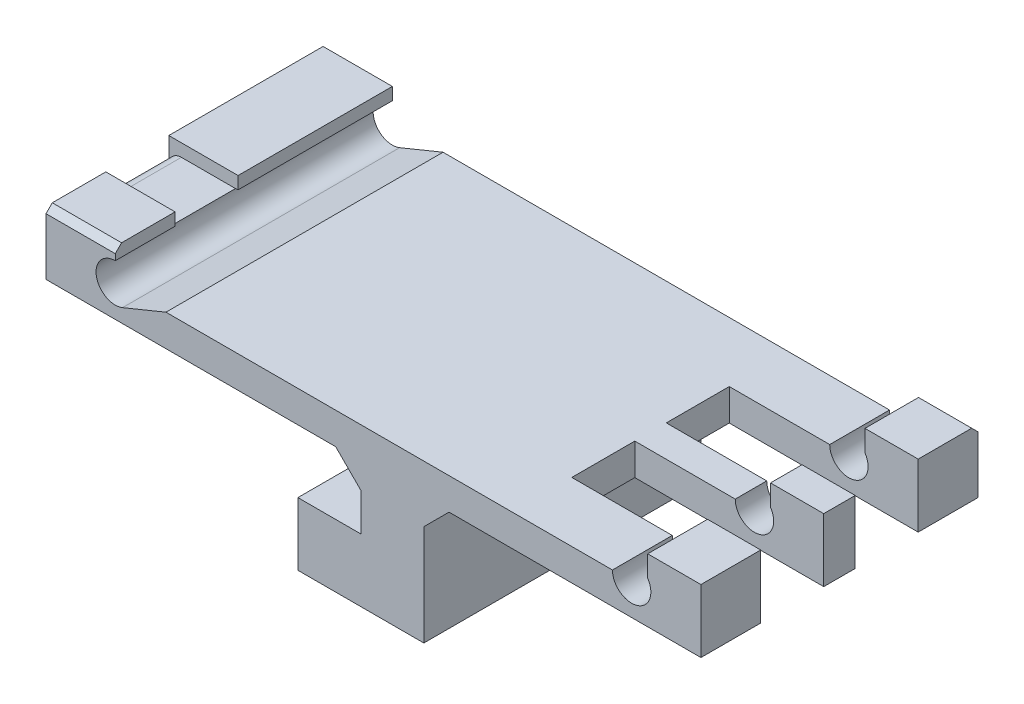
SolidWorks part; units mm, degrees
ref_plane "前视基准面" through (0, 0, 0) normal (0, 0, 1) x (1, 0, 0)
ref_plane "上视基准面" through (0, 0, 0) normal (0, 1, 0) x (1, 0, 0)
ref_plane "右视基准面" through (0, 0, 0) normal (1, 0, 0) x (0, 0, -1)
other "Configuration Table"
sketch "草图1" plane through (0, 0, 0) normal (0, 1, 0) x (1, 0, 0)
  line L1 (-52, -22) -> (52, -22)
  line L2 (-52, -22) -> (-52, 22)
  line L3 (-52, 22) -> (52, 22)
  line L4 (52, -22) -> (52, 22)
  line L5 (-52, -22) -> (52, 22) construction
  line L6 (-52, 22) -> (52, -22) construction
  point P0 (0, 0)
  dimension "D1" = 104
  dimension "D2" = 44
extrude "凸台-拉伸1" add sketch "草图1" along normal blind 10 and the other way blind 0.045
sketch "草图2" plane through (0, 0, -22) normal (0, 0, -1) x (-1, 0, 0)
  line L1 (12, -10.045) -> (2, -10.045)
  line L7 (2, -10.045) -> (2, -0.045)
  line L12 (-52, -0.045) -> (52, -0.045) construction
  line L13 (-8, -0.045) -> (12, -0.045)
  line L14 (-8, -0.045) -> (-8, -20.045)
  line L15 (-8, -20.045) -> (12, -20.045)
  line L16 (12, -0.045) -> (12, -20.045)
  line L17 (52, 10) -> (52, -0.045) construction
  line L18 (-8, -0.045) -> (2, -0.045)
  line L19 (-8, -0.045) -> (-8, -10.5251)
  dimension "D1" = 10
  dimension "D2" = 8
  dimension "D3" = 10
  dimension "D4" = 40
extrude "凸台-拉伸2" add sketch "草图2" against normal up to surface (44 mm away) up to face at (0, 4.9775, 22)
sketch "草图3" plane through (0, 0, 22) normal (0, 0, 1) x (1, 0, 0)
  line L0 (-52, 4.9775) -> (52, 4.9775)
  line L1 (-52, 10) -> (-52, -0.045) construction
  line L2 (52, 10) -> (52, -0.045) construction
  line L3 (0, 0) -> (0, 10) construction
  line L4 (-52, 10) -> (52, 10) construction
  line L6 (-52, 5.0775) -> (52, 5.0775)
  line L7 (-52, 5.0775) -> (-52, 4.8775)
  line L8 (-52, 4.8775) -> (52, 4.8775)
  line L9 (52, 5.0775) -> (52, 4.8775)
  line L10 (-52, 5.0775) -> (52, 4.8775) construction
  line L11 (-52, 4.8775) -> (52, 5.0775) construction
  circle A0 centre (41, 4.9775) radius 3.05
  circle A1 centre (-41, 4.9775) radius 3.05
  point P10 (0, 4.9775)
  dimension "D2" = 6.1
  dimension "D1" = 82
  dimension "D3" = 0.2
extrude "切除-拉伸1" cut sketch "草图3" against normal up to surface (44 mm away) contours L0 A1 L6 | L0 A1 L8 | L8 A1 | L6 A1 | L0 A0 L6 | L0 A0 L8 | L8 A0 | L6 A0 up to face at (-1.2, -4.036, -22)
sketch "草图4" plane through (0, -0.045, 0) normal (0, -1, 0) x (1, 0, 0)
  line L0 (-52, 0) -> (52, 0) construction
  line L5 (-2, -22) -> (-52, -22) construction
  line L7 (52, 22) -> (52, -22) construction
  line L8 (-52, -22) -> (-52, 22) construction
  line L12 (-32, -17) -> (32, -17)
  line L13 (-32, -17) -> (-32, 17)
  line L14 (-32, 17) -> (32, 17)
  line L15 (32, -17) -> (32, 17)
  line L16 (-32, -17) -> (32, 17) construction
  line L17 (-32, 17) -> (32, -17) construction
  line L21 (8, 22) -> (-12, 22)
  line L22 (-12, 22) -> (-12, -22)
  line L23 (-12, -22) -> (8, -22)
  line L24 (8, -22) -> (8, 22)
  line L25 (8, 22) -> (-12, 22)
  line L26 (-12, 22) -> (-12, -22)
  line L27 (-12, -22) -> (8, -22)
  line L28 (8, -22) -> (8, 22)
  point P8 (0, 0)
  dimension "D1" = 20
  dimension "D2" = 20
  dimension "D3" = 5
  dimension "D4" = 0
extrude "切除-拉伸2" [suppressed] cut sketch "草图4" against normal up to surface (10.045 mm away)
sketch "草图6" plane through (37.3205, -20.045, 0) normal (0, 1, 0) x (-1, 0, 0)
  line L5 (34.3205, -17) -> (34.3205, 17)
  line L10 (49.3205, 22) -> (29.3205, 22)
  line L11 (49.3205, -22) -> (49.3205, 22)
  line L12 (29.3205, -22) -> (49.3205, -22)
  line L13 (29.3205, 22) -> (29.3205, -22)
  line L14 (49.3205, 22) -> (29.3205, 22)
  line L15 (49.3205, -22) -> (49.3205, 22)
  line L16 (29.3205, -22) -> (49.3205, -22)
  line L17 (29.3205, 22) -> (29.3205, -22)
  line L18 (5.3205, -17) -> (69.3205, -17)
  line L19 (69.3205, -17) -> (69.3205, 17)
  line L20 (69.3205, 17) -> (5.3205, 17)
  line L21 (5.3205, 17) -> (5.3205, -17)
  line L22 (5.3205, -17) -> (69.3205, -17)
  line L23 (69.3205, -17) -> (69.3205, 17)
  line L24 (69.3205, 17) -> (5.3205, 17)
  line L25 (5.3205, 17) -> (5.3205, -17)
  dimension "D1" = 0
  dimension "D3" = 5
  dimension "D2" = 0
extrude "切除-拉伸3" [suppressed] cut sketch "草图6" along normal up to surface (30.045 mm away) contours L24 L15 L22 L5
chamfer "倒角1" [suppressed] distance 4 angle 45
chamfer "倒角2" [suppressed] distance 4 angle 45
sketch "草图7" plane through (0, -0.045, 0) normal (0, -1, 0) x (1, 0, 0)
  line L1 (46.3158, 18.5731) -> (-46.3158, 18.5731)
  line L2 (46.3158, 18.5731) -> (46.3158, -18.5731)
  line L3 (46.3158, -18.5731) -> (-46.3158, -18.5731)
  line L4 (-46.3158, 18.5731) -> (-46.3158, -18.5731)
  line L5 (46.3158, 18.5731) -> (-46.3158, -18.5731) construction
  line L6 (46.3158, -18.5731) -> (-46.3158, 18.5731) construction
  line L7 (36.0618, 18.5731) -> (-36.0618, 18.5731)
  line L8 (36.0618, 18.5731) -> (36.0618, -18.5731)
  line L9 (36.0618, -18.5731) -> (-36.0618, -18.5731)
  line L10 (-36.0618, 18.5731) -> (-36.0618, -18.5731)
  line L11 (36.0618, 18.5731) -> (-36.0618, -18.5731) construction
  line L12 (36.0618, -18.5731) -> (-36.0618, 18.5731) construction
  point P0 (0, 0)
  point P6 (0, 0)
chamfer "倒角4" distance 4 angle 45 2 edges at (8, -0.045, 0) (-2, -0.045, 0)
sketch "草图8" plane through (0, -0.045, 0) normal (0, -1, 0) x (1, 0, 0)
  line L0 (-52, 0) -> (52, 0) construction
  line L1 (-32, -17) -> (32, -17)
  line L2 (-32, -17) -> (-32, 17)
  line L3 (-32, 17) -> (32, 17)
  line L4 (32, -17) -> (32, 17)
  line L5 (-32, -17) -> (32, 17) construction
  line L6 (-32, 17) -> (32, -17) construction
  line L7 (-47.5, -17) -> (47.5, -17)
  line L8 (-47.5, -17) -> (-47.5, 17)
  line L9 (-47.5, 17) -> (47.5, 17)
  line L10 (47.5, -17) -> (47.5, 17)
  line L11 (-47.5, -17) -> (47.5, 17) construction
  line L12 (-47.5, 17) -> (47.5, -17) construction
  line L13 (-52, -22) -> (-52, 22) construction
  line L14 (52, 22) -> (52, -22) construction
  circle A0 centre (-47.5, 17) radius 1.575
  circle A1 centre (-32, 17) radius 1.575
  circle A2 centre (32, 17) radius 1.575
  circle A3 centre (47.5, 17) radius 1.575
  circle A4 centre (-47.5, -17) radius 1.575
  circle A5 centre (-32, -17) radius 1.575
  circle A6 centre (32, -17) radius 1.575
  circle A7 centre (47.5, -17) radius 1.575
  point P0 (0, 0)
  point P6 (0, 0)
  dimension "D4" = 3.15
  dimension "D1" = 34
  dimension "D2" = 64
  dimension "D3" = 95
extrude "切除-拉伸4" [suppressed] cut sketch "草图8" against normal up to surface (10.045 mm away) contours L9 A1 L2 | L2 A1 L3 | L3 A1 L9 | L9 A2 | L4 A2 L9 | L9 A2 L4 | A6 L7 | A6 L4 L7 | A6 L7 L4 | A5 L1 L7 | A5 L7 L2 | A5 L2 L1
sketch "草图9" plane through (0, -0.045, 0) normal (0, -1, 0) x (1, 0, 0)
  line L0 (52, 22) -> (52, -22) construction
  line L1 (22, 12.5) -> (52, 12.5)
  line L2 (22, 12.5) -> (22, 2.5)
  line L3 (22, 2.5) -> (52, 2.5)
  line L4 (52, 12.5) -> (52, 2.5)
  line L5 (22, 12.5) -> (52, 2.5) construction
  line L6 (22, 2.5) -> (52, 12.5) construction
  line L7 (0, 0) -> (50, 0) construction
  line L9 (22, -2.5) -> (52, -2.5)
  line L10 (22, -2.5) -> (22, -12.5)
  line L11 (22, -12.5) -> (52, -12.5)
  line L12 (52, -2.5) -> (52, -12.5)
  line L13 (22, -2.5) -> (52, -12.5) construction
  line L14 (22, -12.5) -> (52, -2.5) construction
  point P0 (37, 7.5)
  point P11 (37, -7.5)
  dimension "D1" = 10
  dimension "D2" = 30
  dimension "D3" = 10
  dimension "D4" = 5
extrude "切除-拉伸5" cut sketch "草图9" against normal up to surface (10.045 mm away) up to face at (0, 10, 0)
sketch "草图10" plane through (22, 0, 0) normal (1, 0, 0) x (0, 0, -1)
  line L0 (-12.5, 8) -> (-2.5, 8)
  line L4 (-12.5, -0.045) -> (-2.5, -0.045)
  line L5 (-2.5, -0.045) -> (-2.5, 10)
  line L6 (-2.5, 10) -> (-12.5, 10)
  line L7 (-12.5, 10) -> (-12.5, -0.045)
  line L9 (-2.5, -0.045) -> (-2.5, 10)
  line L10 (-2.5, 10) -> (-12.5, 10)
  line L11 (-12.5, 10) -> (-12.5, -0.045)
  line L13 (-12.5, -0.045) -> (-2.5, -0.045)
  line M7 (-2.5, -0.045) -> (-2.5, 10)
  line M8 (-2.5, 10) -> (-12.5, 10)
  line M9 (-12.5, 10) -> (-12.5, -0.045)
  dimension "D2" = 2
  dimension "D1" = 0
extrude "切除-拉伸6" cut sketch "草图10" against normal up to surface (74 mm away) contours L0 M9 M7 M8 up to face at (-52, 4.9775, 0)
sketch "草图12" plane through (0, 0, -22) normal (0, 0, -1) x (-1, 0, 0)
  line L0 (-52, 10) -> (52, 10) construction
  line L1 (-44.05, 10) -> (41, 10)
  line L2 (-44.05, 10) -> (-44.05, 4.9775)
  line L3 (-44.05, 4.9775) -> (41, 4.9775)
  line L4 (41, 10) -> (41, 4.9775)
  line L6 (-44.05, 10) -> (-43.55, 10)
  line L7 (-44.05, 10) -> (-44.05, 4.9775)
  line L8 (-44.05, 4.9775) -> (-43.55, 4.9775)
  line L9 (-43.55, 10) -> (-43.55, 4.9775)
  circle A0 centre (-41, 4.9775) radius 3.05 construction
  point P12 (-43.6112, 10)
  circle M5 centre (41, 4.9775) radius 3.05
  circle M6 centre (-41, 4.9775) radius 3.05
  line M8 (52, 10) -> (-52, 10)
  dimension "D1" = 0.5
extrude "切除-拉伸8" cut sketch "草图12" against normal up to surface (44 mm away) contours L9 L3 L4 M8 M6 M5 up to face at (-37.95, 4.9775, 22)
fillet "圆角1" radius 2 1 edges at (-52, 8, 7.5)
chamfer "倒角5" [suppressed] distance 1.7 angle 45
chamfer "倒角6" distance 1 angle 45 2 edges at (47.775, 10, -22) (-46.5, 10, 22)
sketch "草图11" [suppressed] plane through (0, 10, 0) normal (0, 1, 0) x (1, 0, 0)
  line L0 (30.2391, -13.95) -> (28.4782, -17)
  line L1 (30.4123, -14.25) -> (28.8246, -17)
  line L2 (28.8246, -17) -> (30.4123, -19.75)
  line L3 (30.4123, -19.75) -> (33.5877, -19.75)
  line L4 (33.5877, -19.75) -> (35.1754, -17)
  line L5 (35.1754, -17) -> (33.5877, -14.25)
  line L6 (33.5877, -14.25) -> (30.4123, -14.25)
  line L7 (-35.1754, -17) -> (-33.5877, -19.75)
  line L8 (-33.5877, -19.75) -> (-30.4123, -19.75)
  line L9 (-30.4123, -19.75) -> (-28.8246, -17)
  line L10 (-28.8246, -17) -> (-30.4123, -14.25)
  line L11 (-30.4123, -14.25) -> (-33.5877, -14.25)
  line L12 (-33.5877, -14.25) -> (-35.1754, -17)
  line L13 (-33.5877, 14.25) -> (-30.4123, 14.25)
  line L14 (-30.4123, 14.25) -> (-28.8246, 17)
  line L15 (-28.8246, 17) -> (-30.4123, 19.75)
  line L16 (-30.4123, 19.75) -> (-33.5877, 19.75)
  line L17 (-33.5877, 19.75) -> (-35.1754, 17)
  line L18 (-35.1754, 17) -> (-33.5877, 14.25)
  line L19 (28.8246, 17) -> (30.4123, 14.25)
  line L20 (30.4123, 14.25) -> (33.5877, 14.25)
  line L21 (33.5877, 14.25) -> (35.1754, 17)
  line L22 (35.1754, 17) -> (33.5877, 19.75)
  line L23 (33.5877, 19.75) -> (30.4123, 19.75)
  line L24 (30.4123, 19.75) -> (28.8246, 17)
  line L25 (28.4782, -17) -> (30.2391, -20.05)
  line L26 (30.2391, -20.05) -> (33.7609, -20.05)
  line L27 (33.7609, -20.05) -> (35.5218, -17)
  line L28 (35.5218, -17) -> (33.7609, -13.95)
  line L29 (33.7609, -13.95) -> (30.2391, -13.95)
  line L30 (-35.5218, -17) -> (-33.7609, -20.05)
  line L31 (-33.7609, -20.05) -> (-30.2391, -20.05)
  line L32 (-30.2391, -20.05) -> (-28.4782, -17)
  line L33 (-28.4782, -17) -> (-30.2391, -13.95)
  line L34 (-30.2391, -13.95) -> (-33.7609, -13.95)
  line L35 (-33.7609, -13.95) -> (-35.5218, -17)
  line L36 (-33.7609, 13.95) -> (-30.2391, 13.95)
  line L37 (-30.2391, 13.95) -> (-28.4782, 17)
  line L38 (-28.4782, 17) -> (-30.2391, 20.05)
  line L39 (-30.2391, 20.05) -> (-33.7609, 20.05)
  line L40 (-33.7609, 20.05) -> (-35.5218, 17)
  line L41 (-35.5218, 17) -> (-33.7609, 13.95)
  line L42 (28.4782, 17) -> (30.2391, 13.95)
  line L43 (30.2391, 13.95) -> (33.7609, 13.95)
  line L44 (33.7609, 13.95) -> (35.5218, 17)
  line L45 (35.5218, 17) -> (33.7609, 20.05)
  line L46 (33.7609, 20.05) -> (30.2391, 20.05)
  line L47 (30.2391, 20.05) -> (28.4782, 17)
  circle A0 centre (32, -17) radius 2.75 construction
  circle A1 centre (-32, -17) radius 2.75 construction
  circle A2 centre (-32, 17) radius 2.75 construction
  circle A3 centre (32, 17) radius 2.75 construction
  circle A4 centre (32, -17) radius 3.05 construction
  circle A5 centre (-32, -17) radius 3.05 construction
  circle A6 centre (-32, 17) radius 3.05 construction
  circle A7 centre (32, 17) radius 3.05 construction
  circle M13 centre (-32, -17) radius 1.575
  circle M14 centre (32, -17) radius 1.575
  dimension "D1" = 5.5
  dimension "D2" = 5.5
  dimension "D3" = 5.5
  dimension "D4" = 5.5
  dimension "D5" = 0.3
extrude "切除-拉伸7" [suppressed] cut sketch "草图11" against normal blind 2.5 contours L34 L35 L30 L31 L32 L33 L12 L11 L10 L9 L8 L7 | L11 L12 L7 L8 L9 L10 M13 | M13 | L40 L41 L36 L37 L38 L39 L18 L17 L16 L15 L14 L13 | L17 L18 L13 L14 L15 L16 | L46 L47 L42 L43 L44 L45 L24 L23 L22 L21 L20 L19 | L23 L24 L19 L20 L21 L22 | L28 L29 L0 L25 L26 L27 L6 L5 L4 L3 L2 L1 | L5 L6 L1 L2 L3 L4 M14
chamfer "倒角7" [suppressed] distance 1 angle 45
chamfer "倒角8" [suppressed] distance 3 angle 45
sketch "草图13" plane through (0, 0, 22) normal (0, 0, 1) x (1, 0, 0)
  line L0 (-39.8444, 2.1549) -> (-32.95, 4.9775)
  line L16 (-52, 9) -> (-52, -0.045)
  line L17 (-52, -0.045) -> (-6, -0.045)
  line L18 (-6, -0.045) -> (-2, -4.045)
  line L19 (-2, -4.045) -> (-2, -10.045)
  line L20 (-2, -10.045) -> (-12, -10.045)
  line L21 (-12, -10.045) -> (-12, -20.045)
  line L22 (-12, -20.045) -> (8, -20.045)
  line L23 (8, -20.045) -> (8, -4.045)
  line L24 (8, -4.045) -> (12, -0.045)
  line L25 (12, -0.045) -> (52, -0.045)
  line L26 (52, -0.045) -> (52, 10)
  line L27 (52, 10) -> (43.55, 10)
  line L28 (43.55, 10) -> (43.55, 6.6508)
  line L29 (37.95, 4.9775) -> (-37.95, 4.9775)
  line L30 (-41, 8.0275) -> (-41, 9)
  line L31 (-41, 9) -> (-52, 9)
  line L32 (-52, 9) -> (-52, -0.045)
  line L34 (-6, -0.045) -> (-2, -4.045)
  line L35 (-2, -4.045) -> (-2, -10.045)
  line L36 (-2, -10.045) -> (-12, -10.045)
  line L37 (-12, -10.045) -> (-12, -20.045)
  line L38 (-12, -20.045) -> (8, -20.045)
  line L39 (8, -20.045) -> (8, -4.045)
  line L40 (8, -4.045) -> (12, -0.045)
  line L41 (12, -0.045) -> (52, -0.045)
  line L42 (52, -0.045) -> (52, 10)
  line L43 (52, 10) -> (43.55, 10)
  line L45 (37.95, 4.9775) -> (-37.95, 4.9775)
  line L46 (-41, 8.0275) -> (-41, 9)
  line L47 (-41, 9) -> (-52, 9)
  line L49 (-52, -0.045) -> (-6, -0.045)
  line L50 (43.55, 10) -> (43.55, 6.6508)
  arc A2 (37.95, 4.9775) -> (43.55, 6.6508) centre (41, 4.9775) ccw
  arc A3 (-41, 8.0275) -> (-37.95, 4.9775) centre (-41, 4.9775) ccw
  arc A4 (37.95, 4.9775) -> (43.55, 6.6508) centre (41, 4.9775) ccw
  arc A5 (-41, 8.0275) -> (-37.95, 4.9775) centre (-41, 4.9775) ccw
  line M33 (37.95, 4.9775) -> (-37.95, 4.9775)
  arc M34 (-37.95, 4.9775) -> (-41, 8.0275) centre (-41, 4.9775) cw
  dimension "D2" = 5
  dimension "D1" = 0
extrude "切除-拉伸9" cut sketch "草图13" against normal up to surface (44 mm away) contours L0 M34 M33 up to face at (-0.1921, -0.7365, -22)
